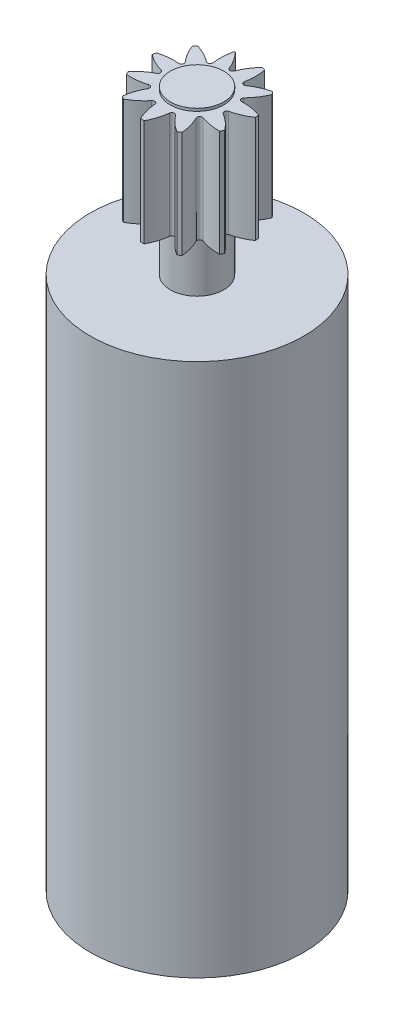
SolidWorks part; units mm, degrees
ref_plane "正面" through (0, 0, 0) normal (0, 0, 1) x (1, 0, 0)
ref_plane "平面" through (0, 0, 0) normal (0, 1, 0) x (1, 0, 0)
ref_plane "右側面" through (0, 0, 0) normal (1, 0, 0) x (0, 0, -1)
sketch "ｽｹｯﾁ1" plane through (0, 0, 0) normal (0, 0, 1) x (1, 0, 0)
  line L0 (0, 0) -> (0, 24.0529) construction
  line L1 (0, 24.0529) -> (0, 0) construction
  line L2 (0, 0) -> (24.7994, 0) construction
  line L3 (0, 0) -> (0, 26.1)
  line L4 (0, 0) -> (4, 0)
  line L5 (4, 0) -> (4, 20)
  line L6 (4, 20) -> (1, 20)
  line L7 (1, 20) -> (1, 22)
  line L8 (1, 22) -> (2, 22)
  line L9 (2, 22) -> (2, 26)
  line L10 (2, 26) -> (1, 26)
  line L11 (1, 26) -> (1, 26.1)
  line L12 (1, 26.1) -> (0, 26.1)
  dimension "D1" = 26.1
  dimension "D2" = 4
  dimension "D3" = 20
  dimension "D4" = 3
  dimension "D5" = 2
  dimension "D6" = 1
  dimension "D7" = 0.1
  dimension "D8" = 1
  dimension "D9" = 4
revolve "回転1" add sketch "ｽｹｯﾁ1" angle 360 about L3
sketch "ｽｹｯﾁ3" plane through (0, 26, 0) normal (0, 1, 0) x (1, 0, 0)
  line L0 (0, 0) -> (0, 5.8055) construction
  arc A0 (0.0929, 1.2999) -> (0.5, 1.9365) centre (1.951, 0.5601) cw
  circle A1 centre (0, 0) radius 1 construction
  circle A2 centre (0, 0) radius 2 construction
  arc A3 (-0.0929, 1.2999) -> (-0.5, 1.9365) centre (-1.951, 0.5601) ccw
  arc A4 (0.0929, 1.2999) -> (-0.0929, 1.2999) centre (0, 1.3369) cw
  arc A5 (-0.5, 1.9365) -> (0.5, 1.9365) centre (0, 0) cw
  point P14 (0, 1)
  dimension "D2" = 2
  dimension "D3" = 2
  dimension "D4" = 0.1
  dimension "D1" = 1
extrude "ｶｯﾄ - 押し出し1" cut sketch "ｽｹｯﾁ3" against normal blind 4.3
pattern_circular "円形ﾊﾟﾀｰﾝ1" count 11 every 33 about axis through (0, 0, 0) along (0, 1, 0) of "ｶｯﾄ - 押し出し1"
